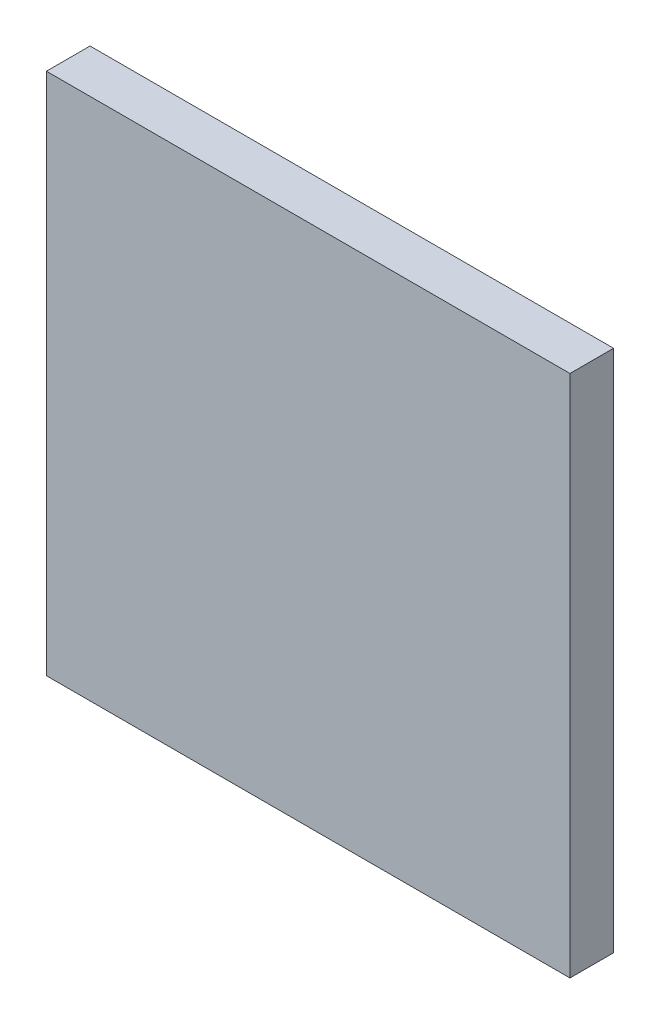
SolidWorks part; units mm, degrees
ref_plane "Front" through (0, 0, 0) normal (0, 0, 1) x (1, 0, 0)
ref_plane "Top" through (0, 0, 0) normal (0, 1, 0) x (1, 0, 0)
ref_plane "Right" through (0, 0, 0) normal (1, 0, 0) x (0, 0, -1)
sketch "Sketch2" plane through (0, 0, 0) normal (0, 0, 1) x (1, 0, 0)
  line L1 (-79.921, 48.6159) -> (-3.721, 48.6159)
  line L2 (-79.921, 48.6159) -> (-79.921, -27.5841)
  line L3 (-79.921, -27.5841) -> (-3.721, -27.5841)
  line L4 (-3.721, 48.6159) -> (-3.721, -27.5841)
  dimension "D1" = 76.2
  dimension "D2" = 76.2
extrude "Boss-Extrude1" add sketch "Sketch2" along normal blind 6.35
